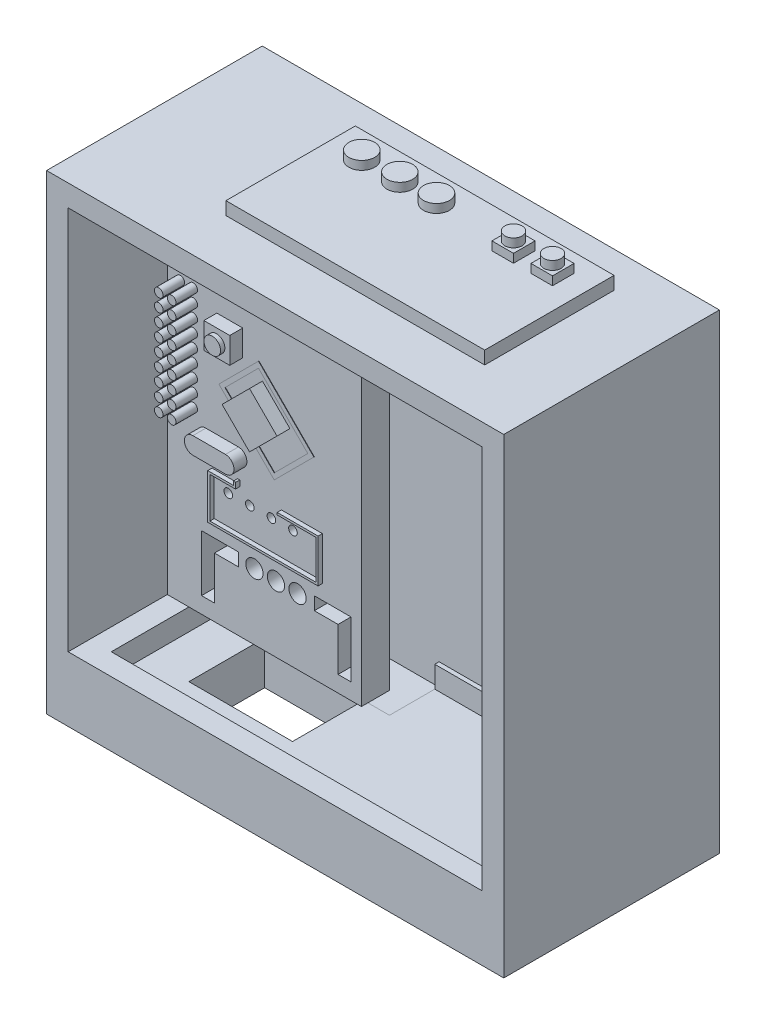
SolidWorks part; units mm, degrees
ref_plane "前基準面" through (0, 0, 0) normal (0, 0, 1) x (1, 0, 0)
ref_plane "上基準面" through (0, 0, 0) normal (0, 1, 0) x (1, 0, 0)
ref_plane "右基準面" through (0, 0, 0) normal (1, 0, 0) x (0, 0, -1)
sketch "草圖1" plane through (0, 0, 0) normal (0, 1, 0) x (1, 0, 0)
  line L1 (-53, 22.5) -> (53, 22.5)
  line L2 (-53, 22.5) -> (-53, -22.5)
  line L3 (-53, -22.5) -> (53, -22.5)
  line L4 (53, 22.5) -> (53, -22.5)
  line L5 (-53, 22.5) -> (53, -22.5) construction
  line L6 (-53, -22.5) -> (53, 22.5) construction
  point P0 (0, 0)
  dimension "D1" = 106
  dimension "D2" = 45
extrude "填料-伸長1" add sketch "草圖1" along normal blind 200
sketch "草圖2" plane through (0, 0, 22.5) normal (0, 0, 1) x (1, 0, 0)
  line L0 (-53, 200) -> (-53, 0) construction
  line L1 (-43, 190) -> (43, 190)
  line L2 (-43, 190) -> (-43, 10)
  line L3 (-43, 10) -> (43, 10)
  line L4 (43, 190) -> (43, 10)
  line L5 (-53, 200) -> (53, 200) construction
  line L6 (53, 200) -> (53, 0) construction
  line L7 (-53, 0) -> (53, 0) construction
  dimension "D1" = 10
  dimension "D2" = 10
  dimension "D3" = 10
  dimension "D4" = 10
extrude "除料-伸長1" cut sketch "草圖2" against normal blind 35
sketch "草圖4" plane through (0, 0, 0) normal (0, -1, 0) x (1, 0, 0)
  line L0 (-53, -22.5) -> (-53, 22.5) construction
  line L1 (-33, 14.5) -> (-8.9694, 14.5)
  line L2 (-33, 14.5) -> (-33, 7.292)
  line L3 (-33, 7.292) -> (-8.9694, 7.292)
  line L4 (-8.9694, 14.5) -> (-8.9694, 7.292)
  line L5 (-53, 22.5) -> (53, 22.5) construction
  dimension "D1" = 20
  dimension "D2" = 8
extrude "除料-伸長4" cut sketch "草圖4" against normal blind 35
sketch "草圖5" plane through (0, 0, 22.5) normal (0, 0, 1) x (1, 0, 0)
  line L1 (-53, 200) -> (53, 200)
  line L2 (-53, 200) -> (-53, 0)
  line L3 (-53, 0) -> (53, 0)
  line L4 (53, 200) -> (53, 0)
extrude "填料-伸長2" add sketch "草圖5" along normal blind 5
sketch "草圖6" plane through (0, 0, 27.5) normal (0, 0, 1) x (1, 0, 0)
  line L0 (-53, 200) -> (-53, 0) construction
  line L1 (-48, 195) -> (48, 195)
  line L2 (-48, 195) -> (-48, 15)
  line L3 (-48, 15) -> (48, 15)
  line L4 (48, 195) -> (48, 15)
  line L5 (53, 200) -> (-53, 200) construction
  line L6 (53, 0) -> (53, 200) construction
  line L7 (-53, 0) -> (53, 0) construction
  dimension "D1" = 5
  dimension "D2" = 5
  dimension "D3" = 5
  dimension "D4" = 15
extrude "除料-伸長5" cut sketch "草圖6" against normal blind 41
sketch "草圖7" plane through (0, 0, -13.5) normal (0, 0, 1) x (1, 0, 0)
  line L0 (-48, 195) -> (-48, 15) construction
  line L1 (-48, 85) -> (-3, 85)
  line L2 (-48, 85) -> (-48, 15)
  line L3 (-48, 15) -> (-3, 15)
  line L4 (-3, 85) -> (-3, 15)
  line L5 (-48, 15) -> (48, 15) construction
  dimension "D1" = 70
  dimension "D2" = 45
extrude "填料-伸長3" add sketch "草圖7" along normal blind 18
sketch "草圖8" plane through (0, 0, 0) normal (0, -1, 0) x (1, 0, 0)
  line L1 (-33, 14.5) -> (-8.9694, 14.5)
  line L2 (-33, 14.5) -> (-33, -3.0598)
  line L3 (-33, -3.0598) -> (-8.9694, -3.0598)
  line L4 (-8.9694, 14.5) -> (-8.9694, -3.0598)
extrude "除料-伸長6" cut sketch "草圖8" against normal blind 15
sketch "草圖9" plane through (0, 0, -13.5) normal (0, 0, 1) x (1, 0, 0)
  line L0 (-34, -815) -> (-34, 49185) construction
  line L2 (34, -815) -> (34, 49185) construction
  line L4 (-48, 195) -> (-48, 15) construction
  line L5 (48, 15) -> (48, 195) construction
  line L6 (-1038, 185) -> (48962, 185) construction
  line L7 (-1038, 175) -> (48962, 175) construction
  line L9 (48, 195) -> (-48, 195) construction
  line L10 (48, 195) -> (-48, 195) construction
  circle A0 centre (-34, 185) radius 3.5
  circle A1 centre (-34, 175) radius 3.5
  circle A2 centre (34, 185) radius 3.5
  circle A3 centre (34, 175) radius 3.5
  dimension "D5" = 7
  dimension "D6" = 7
  dimension "D7" = 7
  dimension "D8" = 7
  dimension "D1" = 14
  dimension "D2" = 14
  dimension "D3" = 10
  dimension "D4" = 20
extrude "除料-伸長7" cut sketch "草圖9" against normal through all
sketch "草圖11" plane through (0, 0, 4.5) normal (0, 0, 1) x (1, 0, 0)
  line L1 (-36.5315, 77.2499) -> (-30.5315, 77.2499)
  line L2 (-36.5315, 77.2499) -> (-36.5315, 71.2499)
  line L3 (-36.5315, 71.2499) -> (-30.5315, 71.2499)
  line L4 (-30.5315, 77.2499) -> (-30.5315, 71.2499)
  circle A0 centre (-33.5925, 74.1521) radius 1.9254
  dimension "D1" = 6
  dimension "D2" = 6
extrude "填料-伸長5" add sketch "草圖11" along normal blind 3
sketch "草圖12" plane through (0, 0, 7.5) normal (0, 0, 1) x (1, 0, 0)
  circle A0 centre (-33.5925, 74.1521) radius 1.9254
extrude "填料-伸長6" add sketch "草圖12" along normal blind 1 separate body
sketch "草圖14" plane through (0, 0, 4.5) normal (0, 0, 1) x (1, 0, 0)
  line L1 (-32.3103, 62.5201) -> (-25.9463, 68.884)
  line L2 (-32.3103, 62.5201) -> (-25.9463, 56.1561)
  line L3 (-25.9463, 56.1561) -> (-19.5824, 62.5201)
  line L4 (-25.9463, 68.884) -> (-19.5824, 62.5201)
  dimension "D1" = 9
  dimension "D2" = 9
extrude "填料-伸長7" add sketch "草圖14" along normal blind 3
sketch "草圖22" plane through (0, 0, 4.5) normal (0, 0, 1) x (1, 0, 0)
  line L0 (-39.0776, 50.8915) -> (-31.5286, 50.8915) construction
  line L1 (-39.0776, 52.8686) -> (-31.5286, 52.8686)
  line L2 (-39.0776, 48.9143) -> (-31.5286, 48.9143)
  arc A0 (-39.0776, 52.8686) -> (-39.0776, 48.9143) centre (-39.0776, 50.8915) ccw
  arc A1 (-31.5286, 48.9143) -> (-31.5286, 52.8686) centre (-31.5286, 50.8915) ccw
  point P2 (-35.3031, 50.8915)
extrude "填料-伸長12" add sketch "草圖22" along normal blind 3
sketch "草圖23" plane through (0, 0, 4.5) normal (0, 0, 1) x (1, 0, 0)
  line L0 (-40.0744, 18.7432) -> (-37.0744, 18.7432)
  line L1 (-37.0744, 18.7432) -> (-37.0744, 28.7885)
  line L2 (-37.0744, 28.7885) -> (-31.4645, 28.7885)
  line L3 (-31.4645, 28.7885) -> (-31.4645, 31.7885)
  line L4 (-31.4645, 31.7885) -> (-40.0744, 31.7885)
  line L5 (-40.0744, 31.7885) -> (-40.0744, 18.7432)
  line L6 (-1031.4645, 30.2885) -> (48968.5355, 30.2885) construction
  line L7 (-1037.0744, 28.7885) -> (48962.9256, 28.7885) construction
  line L8 (-1037.0744, 18.7432) -> (48962.9256, 18.7432) construction
  line L9 (-8.4235, 18.7432) -> (-5.4235, 18.7432)
  line L10 (-5.4235, 18.7432) -> (-5.4235, 31.7885)
  line L11 (-5.4235, 31.7885) -> (-13.9289, 31.7885)
  line L12 (-13.9289, 31.7885) -> (-13.9289, 28.7885)
  line L13 (-13.9289, 28.7885) -> (-8.4235, 28.7885)
  line L14 (-8.4235, 28.7885) -> (-8.4235, 18.7432)
  circle A0 centre (-27.8147, 30.2885) radius 2
  circle A1 centre (-22.8147, 30.2885) radius 2
  circle A2 centre (-17.8147, 30.2885) radius 2
  point P9 (-31.4645, 30.2885)
  dimension "D3" = 4
  dimension "D4" = 4
  dimension "D5" = 5
  dimension "D6" = 5
  dimension "D7" = 4
  dimension "D1" = 3
  dimension "D2" = 3
  dimension "D8" = 8.6099
  dimension "D9" = 3
  dimension "D10" = 3
  dimension "D11" = 3
  dimension "D12" = 3
extrude "除料-伸長8" cut sketch "草圖23" against normal blind 12
sketch "草圖24" plane through (0, 0, 4.5) normal (0, 0, 1) x (1, 0, 0)
  line L0 (-26.7611, 71.1131) -> (-34.5393, 63.3349)
  line L1 (-34.5393, 63.3349) -> (-23.1179, 51.9135)
  line L2 (-23.1179, 51.9135) -> (-15.3397, 59.6916)
  line L3 (-15.3397, 59.6916) -> (-26.7611, 71.1131)
  line L4 (-19.5824, 62.5201) -> (-25.9463, 68.884) construction
  line L5 (-32.3103, 62.5201) -> (-25.9463, 56.1561) construction
  line L6 (-25.9463, 56.1561) -> (-19.5824, 62.5201) construction
  point P10 (-22.7643, 59.3381)
  dimension "D1" = 1
  dimension "D2" = 1
  dimension "D3" = 5
extrude "伸長-薄件1" add sketch "草圖24" along normal blind 0.1 thin
sketch "草圖25" plane through (0, 85, 0) normal (0, 1, 0) x (1, 0, 0)
  line L0 (-48, -4.5) -> (-48, 13.5) construction
  line L1 (-3, 13.5) -> (-48, 13.5)
  line L2 (-3, 13.5) -> (-3, 8.5)
  line L3 (-3, 8.5) -> (-48, 8.5)
  line L4 (-48, 13.5) -> (-48, 8.5)
  dimension "D1" = 5
extrude "除料-伸長9" cut sketch "草圖25" against normal blind 75.1
sketch "草圖26" plane through (0, 85, 0) normal (0, 1, 0) x (1, 0, 0)
  line L0 (-48, -4.5) -> (-48, 8.5) construction
  line L1 (-3, 8.5) -> (-48, 8.5)
  line L2 (-3, 8.5) -> (-3, 2)
  line L3 (-3, 2) -> (-48, 2)
  line L4 (-48, 8.5) -> (-48, 2)
extrude "除料-伸長10" cut sketch "草圖26" against normal blind 75.1
sketch "草圖10" plane through (0, 0, 4.5) normal (0, 0, 1) x (1, 0, 0)
  line L0 (-45, -915) -> (-45, 49085) construction
  line L2 (-6, -915) -> (-6, 49085) construction
  line L4 (-48, 195) -> (-48, 15) construction
  line L5 (-3, 15) -> (-3, 85) construction
  line L6 (-42, -915) -> (-42, 49085) construction
  line L8 (-9, -915) -> (-9, 49085) construction
  circle A0 centre (-45, 79.5958) radius 1
  circle A1 centre (-42, 79.5958) radius 1
  circle A2 centre (-45, 76.5958) radius 1
  circle A3 centre (-42, 76.5958) radius 1
  circle A4 centre (-45, 73.5958) radius 1
  circle A5 centre (-42, 73.5958) radius 1
  circle A6 centre (-45, 70.5958) radius 1
  circle A7 centre (-42, 70.5958) radius 1
  circle A8 centre (-45, 67.5958) radius 1
  circle A9 centre (-42, 67.5958) radius 1
  circle A10 centre (-45, 64.5958) radius 1
  circle A11 centre (-42, 64.5958) radius 1
  circle A12 centre (-45, 61.5958) radius 1
  circle A13 centre (-42, 61.5958) radius 1
  circle A14 centre (-45, 58.5958) radius 1
  circle A15 centre (-42, 58.5958) radius 1
  circle A16 centre (-45, 55.5958) radius 1
  circle A17 centre (-42, 55.5958) radius 1
  dimension "D5" = 2
  dimension "D6" = 2
  dimension "D7" = 2
  dimension "D8" = 2
  dimension "D9" = 2
  dimension "D10" = 2
  dimension "D11" = 2
  dimension "D12" = 2
  dimension "D13" = 2
  dimension "D14" = 2
  dimension "D15" = 2
  dimension "D16" = 2
  dimension "D17" = 3
  dimension "D18" = 3
  dimension "D19" = 3
  dimension "D20" = 3
  dimension "D21" = 3
  dimension "D22" = 3
  dimension "D23" = 3
  dimension "D24" = 3
  dimension "D25" = 3
  dimension "D26" = 3
  dimension "D27" = 2
  dimension "D28" = 2
  dimension "D29" = 2
  dimension "D30" = 2
  dimension "D31" = 2
  dimension "D32" = 2
  dimension "D33" = 3
  dimension "D34" = 3
  dimension "D35" = 3
  dimension "D36" = 3
  dimension "D37" = 3
  dimension "D38" = 3
  dimension "D1" = 3
  dimension "D2" = 3
  dimension "D3" = 3
  dimension "D4" = 3
extrude "填料-伸長4" add sketch "草圖10" along normal blind 5 and the other way blind 15.1
sketch "草圖27" plane through (0, 0, 4.5) normal (0, 0, 1) x (1, 0, 0)
  line L0 (-31.2039, 46.4183) -> (-31.2039, 45.0646)
  line L1 (-31.2039, 45.0646) -> (-37.1353, 45.0646)
  line L2 (-37.1353, 45.0646) -> (-37.1353, 35.6847)
  line L3 (-37.1353, 35.6847) -> (-12.5618, 35.6847)
  line L4 (-12.5618, 35.6847) -> (-12.5618, 44.7108)
  line L5 (-12.5618, 44.7108) -> (-21.5487, 44.7108)
  line L6 (-21.5487, 44.7108) -> (-21.5487, 45.2108)
  line L7 (-21.5487, 45.2108) -> (-12.0618, 45.2108)
  line L8 (-12.0618, 45.2108) -> (-12.0618, 35.1847)
  line L9 (-12.0618, 35.1847) -> (-37.6353, 35.1847)
  line L10 (-37.6353, 35.1847) -> (-37.6353, 45.5646)
  line L11 (-37.6353, 45.5646) -> (-31.7039, 45.5646)
  line L12 (-31.7039, 45.5646) -> (-31.7039, 46.4183)
  line L13 (-31.7039, 46.4183) -> (-31.2039, 46.4183)
  dimension "D1" = 0.5
  dimension "D2" = 0.5
  dimension "D3" = 0.5
  dimension "D4" = 0.5
  dimension "D5" = 0.5
  dimension "D6" = 0.5
extrude "填料-伸長14" add sketch "草圖27" along normal blind 1
sketch "草圖28" plane through (0, 0, 4.5) normal (0, 0, 1) x (1, 0, 0)
  line L0 (-1037.1353, 42.4079) -> (48962.8647, 42.4079) construction
  circle A0 centre (-33.8755, 42.4079) radius 1
  circle A1 centre (-28.8755, 42.4079) radius 1
  circle A2 centre (-23.8755, 42.4079) radius 1
  circle A3 centre (-18.8755, 42.4079) radius 1
  dimension "D1" = 2
  dimension "D2" = 2
  dimension "D3" = 2
  dimension "D4" = 2
  dimension "D5" = 5
  dimension "D6" = 5
  dimension "D7" = 5
extrude "除料-伸長11" cut sketch "草圖28" against normal blind 12.1
sketch "草圖39" plane through (0, 10, 0) normal (0, 1, 0) x (1, 0, 0)
  line L0 (43, -22.5) -> (43, 12.5) construction
  line L1 (-3, 12.5) -> (43, 12.5) construction
  circle A0 centre (36, 5.5) radius 6
  dimension "D1" = 12
  dimension "D2" = 7
  dimension "D3" = 7
extrude "填料-伸長22" add sketch "草圖39" along normal blind 60
sketch "草圖40" plane through (0, 70, 0) normal (0, 1, 0) x (1, 0, 0)
  line L1 (32.4604, 3.9294) -> (39.8369, 3.9294)
  line L2 (32.4604, 3.9294) -> (32.4604, 2.0018)
  line L3 (32.4604, 2.0018) -> (39.8369, 2.0018)
  line L4 (39.8369, 3.9294) -> (39.8369, 2.0018)
extrude "除料-伸長12" cut sketch "草圖40" against normal blind 23
sketch "草圖41" plane through (0, 70, 0) normal (0, 1, 0) x (1, 0, 0)
  line L1 (33.7325, 8.9297) -> (37.9957, 8.9297)
  line L2 (33.7325, 8.9297) -> (33.7325, 7.4469)
  line L3 (33.7325, 7.4469) -> (37.9957, 7.4469)
  line L4 (37.9957, 8.9297) -> (37.9957, 7.4469)
extrude "除料-伸長13" cut sketch "草圖41" against normal blind 23
sketch "草圖42" plane through (0, 0, 0) normal (0, 1, 0) x (1, 0, 0)
  line L0 (-59.7493, -30.1122) -> (-55.7853, -34.0763)
  line L1 (-55.7853, -34.0763) -> (-109.1584, -87.4494)
  line L2 (-109.1584, -87.4494) -> (-113.1224, -83.4853)
  line L3 (-113.1224, -83.4853) -> (-59.7493, -30.1122)
extrude "填料-伸長23" add sketch "草圖42" along normal blind 200 separate body
sketch "草圖43" plane through (0, 200, 0) normal (0, 1, 0) x (1, 0, 0)
  circle A0 centre (-56.349, -28.8579) radius 5.3338
extrude "填料-伸長24" add sketch "草圖43" against normal blind 200
sketch "草圖45" plane through (0, 200, 0) normal (0, 1, 0) x (1, 0, 0)
  line L0 (-51.1909, -27.5) -> (-45.6225, -33.0684)
  line L1 (-45.6225, -33.0684) -> (-108.6096, -96.0556)
  line L2 (-108.6096, -96.0556) -> (-126.7933, -77.872)
  line L3 (-126.7933, -77.872) -> (-59.1056, -19.5853)
  line L4 (-59.1056, -19.5853) -> (-53, -24.7065)
  line L5 (-53, -24.7065) -> (-53, -27.5)
  line L6 (-53, -27.5) -> (-51.1909, -27.5)
extrude "除料-伸長14" cut sketch "草圖45" against normal blind 207
sketch "草圖48" plane through (0, 0, 27.5) normal (0, 0, 1) x (1, 0, 0)
  line L0 (53, 0) -> (53, 200) construction
  line L1 (-53, 200) -> (53, 200)
  line L2 (-53, 200) -> (-53, 104.1393)
  line L3 (-53, 104.1393) -> (53, 104.1393)
  line L4 (53, 200) -> (53, 104.1393)
extrude "除料-伸長17" cut sketch "草圖48" against normal through all
sketch "草圖49" plane through (0, 104.1393, 0) normal (0, 1, 0) x (1, 0, 0)
  line L1 (-53, -27.5) -> (53, -27.5)
  line L2 (-53, -27.5) -> (-53, 22.5)
  line L3 (-53, 22.5) -> (53, 22.5)
  line L4 (53, -27.5) -> (53, 22.5)
extrude "填料-伸長25" add sketch "草圖49" along normal blind 5
sketch "草圖50" plane through (0, 109.1393, 0) normal (0, 1, 0) x (1, 0, 0)
  line L1 (-23.1567, 14.2364) -> (36.8433, 14.2364)
  line L2 (-23.1567, 14.2364) -> (-23.1567, -15.7636)
  line L3 (-23.1567, -15.7636) -> (36.8433, -15.7636)
  line L4 (36.8433, 14.2364) -> (36.8433, -15.7636)
  dimension "D1" = 60
  dimension "D2" = 30
extrude "填料-伸長26" add sketch "草圖50" along normal blind 3
sketch "草圖51" plane through (0, 112.1393, 0) normal (0, 1, 0) x (1, 0, 0)
  line L0 (-1023.1567, 8.1874) -> (48976.8433, 8.1874) construction
  circle A0 centre (-15.607, 8.1874) radius 3
  point P4 (0, 0)
  dimension "D1" = 6
extrude "填料-伸長27" add sketch "草圖51" along normal blind 2
sketch "草圖52" plane through (0, 112.1393, 0) normal (0, 1, 0) x (1, 0, 0)
  line L0 (-1012.607, 8.1874) -> (48987.393, 8.1874) construction
  circle A2 centre (-6.7856, 8.1874) radius 2.9858
  dimension "D1" = 5.9715
extrude "填料-伸長28" add sketch "草圖52" along normal blind 2
sketch "草圖53" plane through (0, 112.1393, 0) normal (0, 1, 0) x (1, 0, 0)
  line L0 (-1002.0855, 8.1874) -> (48997.9145, 8.1874) construction
  circle A1 centre (1.7144, 8.1874) radius 3
  circle A2 centre (-6.7856, 8.1874) radius 2.9858 construction
  dimension "D1" = 6
  dimension "D2" = 8.5
extrude "填料-伸長29" add sketch "草圖53" along normal blind 2
sketch "草圖54" plane through (0, 112.1393, 0) normal (0, 1, 0) x (1, 0, 0)
  line L1 (17.7557, 9.9969) -> (22.7557, 9.9969)
  line L2 (17.7557, 9.9969) -> (17.7557, 4.9969)
  line L3 (17.7557, 4.9969) -> (22.7557, 4.9969)
  line L4 (22.7557, 9.9969) -> (22.7557, 4.9969)
  line L5 (26.8033, 9.9969) -> (31.8033, 9.9969)
  line L6 (26.8033, 9.9969) -> (26.8033, 4.9969)
  line L7 (26.8033, 4.9969) -> (31.8033, 4.9969)
  line L8 (31.8033, 9.9969) -> (31.8033, 4.9969)
  dimension "D1" = 5
  dimension "D2" = 5
  dimension "D3" = 5
  dimension "D4" = 5
extrude "填料-伸長30" add sketch "草圖54" along normal blind 2
sketch "草圖55" plane through (0, 114.1393, 0) normal (0, 1, 0) x (1, 0, 0)
  line L0 (-968.1967, 7.4969) -> (49031.8033, 7.4969) construction
  line L1 (31.8033, 4.9969) -> (31.8033, 9.9969) construction
  line L2 (17.7557, 9.9969) -> (17.7557, 4.9969) construction
  line L3 (26.8033, 9.9969) -> (26.8033, 4.9969) construction
  circle A0 centre (29.3033, 7.4969) radius 2
  circle A1 centre (20.2557, 7.4969) radius 2
  point P5 (31.8033, 7.4969)
  dimension "D1" = 4
  dimension "D2" = 4
  dimension "D3" = 2.5
  dimension "D4" = 2.5
extrude "填料-伸長31" add sketch "草圖55" along normal blind 2
